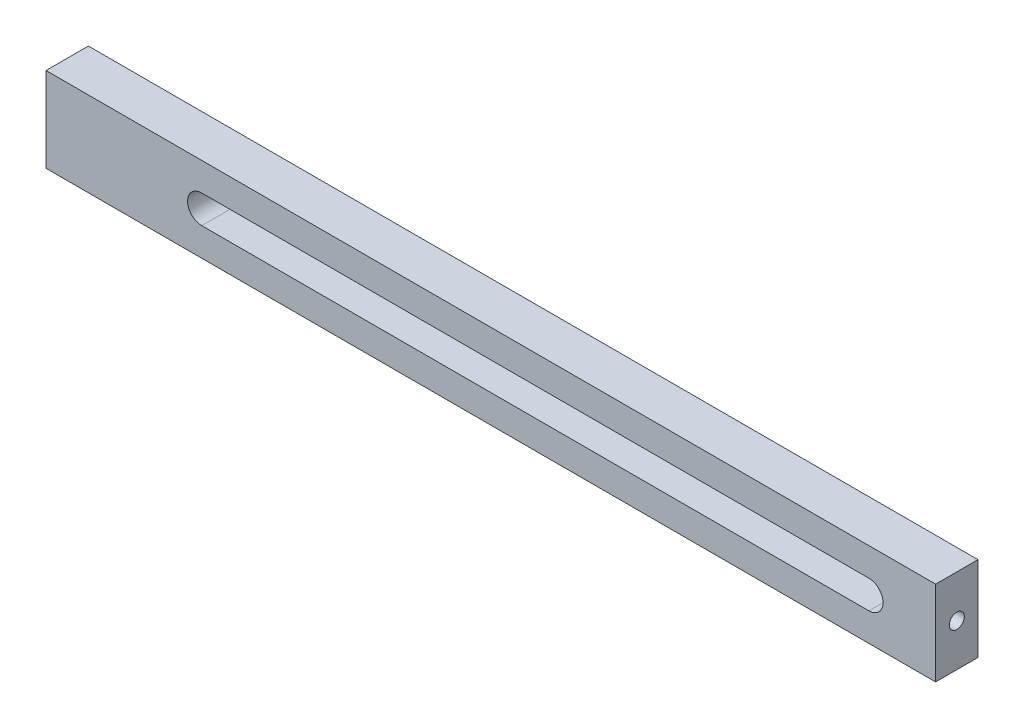
SolidWorks part; units mm, degrees
ref_plane "Alzado" through (0, 0, 0) normal (0, 0, 1) x (1, 0, 0)
ref_plane "Planta" through (0, 0, 0) normal (0, 1, 0) x (1, 0, 0)
ref_plane "Vista lateral" through (0, 0, 0) normal (1, 0, 0) x (0, 0, -1)
sketch "Croquis1" plane through (0, 0, 0) normal (0, 0, 1) x (1, 0, 0)
  line L0 (-130, 0) -> (170, 0) construction
  line L1 (-200, -19.05) -> (200, -19.05)
  line L2 (-200, -19.05) -> (-200, 19.05)
  line L3 (-200, 19.05) -> (200, 19.05)
  line L4 (200, -19.05) -> (200, 19.05)
  line L5 (-200, -19.05) -> (200, 19.05) construction
  line L6 (-200, 19.05) -> (200, -19.05) construction
  line L7 (-130, 6.35) -> (170, 6.35)
  line L8 (-130, -6.35) -> (170, -6.35)
  arc A0 (-130, 6.35) -> (-130, -6.35) centre (-130, 0) ccw
  arc A1 (170, -6.35) -> (170, 6.35) centre (170, 0) ccw
  point P0 (0, 0)
  point P8 (20, 0)
  dimension "D1" = 38.1
  dimension "D2" = 400
  dimension "D3" = 300
  dimension "D4" = 30
  dimension "D5" = 12.7
extrude "Saliente-Extruir1" add sketch "Croquis1" along normal mid plane 19.05
hole_wizard "Taladro de margen para 1/41" positions "Croquis2" profile "Croquis3" hole size "1/4" standard "Ansi Inch"
sketch "Croquis2" plane through (200, 0, 0) normal (1, 0, 0) x (0, 0, -1)
  point P0 (0, 0)
sketch "Croquis3" plane through (200, 0, 0) normal (0, 1, 0) x (0, 0, -1)
  line L0 (0, 0) -> (0, 23.65)
  line L1 (0, 23.65) -> (3.3782, 23.65)
  line L2 (3.3782, 23.65) -> (3.3782, 0)
  line L5 (3.3782, 0) -> (0, 0)
  line L11 (0, -6.35) -> (0, 107.95) construction
  dimension "Diámetro de taladro hasta el siguiente" = 6.7564
  dimension "Profundidad de taladro hasta el siguiente" = 23.65
hole_wizard "Taladro roscado 7/16-141" positions "Croquis4" profile "Croquis5" tap size "7/16-14" standard "Ansi Inch"
sketch "Croquis4" plane through (-200, 0, 0) normal (-1, 0, 0) x (0, 0, 1)
  line L0 (0, 0) -> (-50000, 0) construction
  point P0 (0, 9)
  point P2 (0, -9)
  point P8 (0, 0)
  dimension "D1" = 9
sketch "Croquis5" plane through (-200, 9, 0) normal (0, 1, 0) x (0, 0, 1)
  line L0 (0, 0) -> (0, 22.8082)
  line L1 (0, 22.8082) -> (4.6736, 20)
  line L2 (4.6736, 20) -> (4.6736, 0)
  line L5 (4.6736, 0) -> (0, 0)
  line L10 (0, 22.8082) -> (-4.6736, 20) construction
  line L11 (0, -6.35) -> (0, 107.95) construction
  dimension "Diámetro de perforador para roscar" = 9.3472
  dimension "Profundidad de perforador para roscar" = 20
  dimension "Ángulo de perforador" = 118
